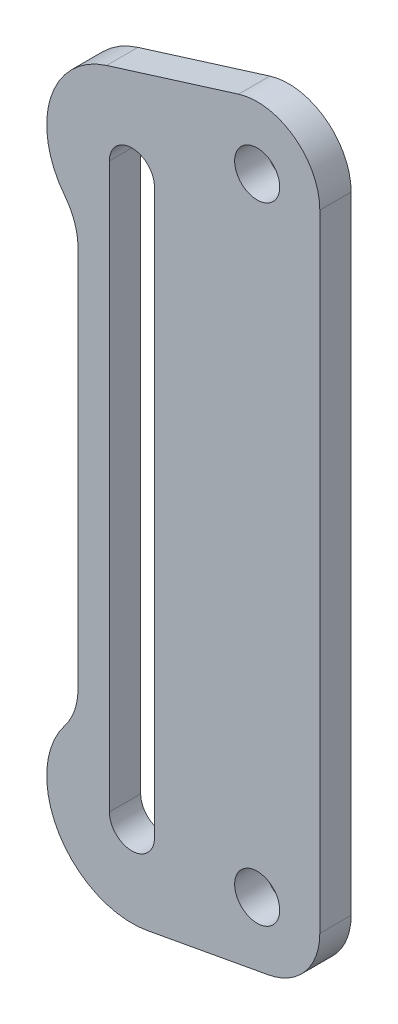
SolidWorks part; units mm, degrees
ref_plane "Front Plane" through (0, 0, 0) normal (0, 0, 1) x (1, 0, 0)
ref_plane "Top Plane" through (0, 0, 0) normal (0, 1, 0) x (1, 0, 0)
ref_plane "Right Plane" through (0, 0, 0) normal (1, 0, 0) x (0, 0, -1)
sketch "Sketch1" plane through (0, 0, 0) normal (0, 0, 1) x (1, 0, 0)
  line L0 (-12.7, 0) -> (-12.7, 57.15) construction
  line L1 (-14.986, 0) -> (-14.986, 57.15)
  line L2 (-10.414, 0) -> (-10.414, 57.15)
  line L3 (-12.7, 57.15) -> (-12.7, 0) construction
  line L6 (-11.1455, -8.4949) -> (1.143, -6.2463)
  line L7 (6.35, 63.5) -> (6.35, 0)
  line L8 (-15.2682, 65.3953) -> (-1.8884, 69.5627)
  line L9 (-18.161, 50.4599) -> (-18.161, 6.6901)
  circle A0 centre (0, 0) radius 2.286
  circle A1 centre (0, 63.5) radius 2.286
  arc A2 (-14.986, 0) -> (-10.414, 0) centre (-12.7, 0) ccw
  arc A3 (-10.414, 57.15) -> (-14.986, 57.15) centre (-12.7, 57.15) ccw
  arc A4 (-15.2682, 65.3953) -> (-18.161, 50.4599) centre (-12.7, 57.15) ccw
  arc A5 (-18.161, 6.6901) -> (-11.1455, -8.4949) centre (-12.7, 0) ccw
  arc A7 (1.143, -6.2463) -> (6.35, 0) centre (0, 0) ccw
  arc A8 (6.35, 63.5) -> (-1.8884, 69.5627) centre (0, 63.5) ccw
  point P7 (-12.7, 28.575)
  point P12 (-9.525, 41.275)
  point P13 (0, 0)
  dimension "D2" = 4.572
  dimension "D3" = 4.572
  dimension "D7" = 6.35
  dimension "D8" = 6.35
  dimension "D9" = 6.35
  dimension "D1" = 4.572
  dimension "D5" = 12.7
  dimension "D6" = 63.5
  dimension "D10" = 3.175
  dimension "D11" = 6.35
extrude "Boss-Extrude1" add sketch "Sketch1" along normal blind 3.175
fillet "Fillet1" radius 6.35 2 edges at (-18.161, 50.4599, 1.5875) (-18.161, 6.6901, 1.5875)
